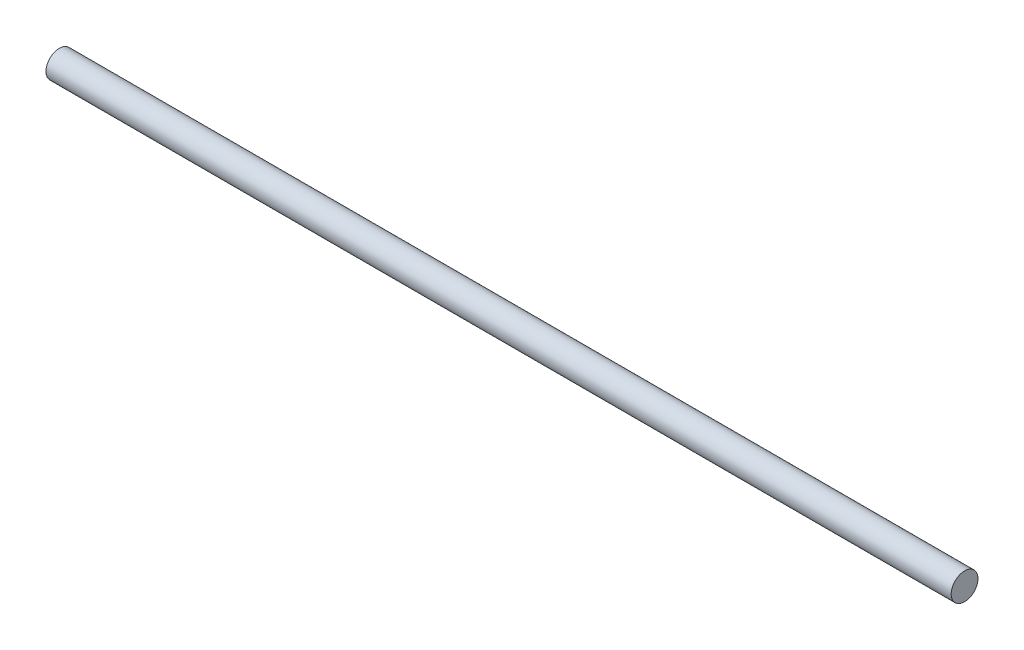
SolidWorks part; units mm, degrees
ref_plane "Front Plane" through (0, 0, 0) normal (0, 0, 1) x (1, 0, 0)
ref_plane "Top Plane" through (0, 0, 0) normal (0, 1, 0) x (1, 0, 0)
ref_plane "Right Plane" through (0, 0, 0) normal (1, 0, 0) x (0, 0, -1)
sketch "Sketch1" plane through (0, 0, 0) normal (1, 0, 0) x (0, 0, -1)
  line L0 (0.3662, 0) -> (32.5897, 0) construction
  circle A0 centre (0, 0) radius 4
extrude "Boss-Extrude1" add sketch "Sketch1" along normal blind 270
sketch "Sketch2" plane through (0, 0, 0) normal (-1, 0, 0) x (0, 0, 1)
  circle A0 centre (0, 0) radius 2.626
extrude "Cut-Extrude1" cut sketch "Sketch2" against normal blind 40
